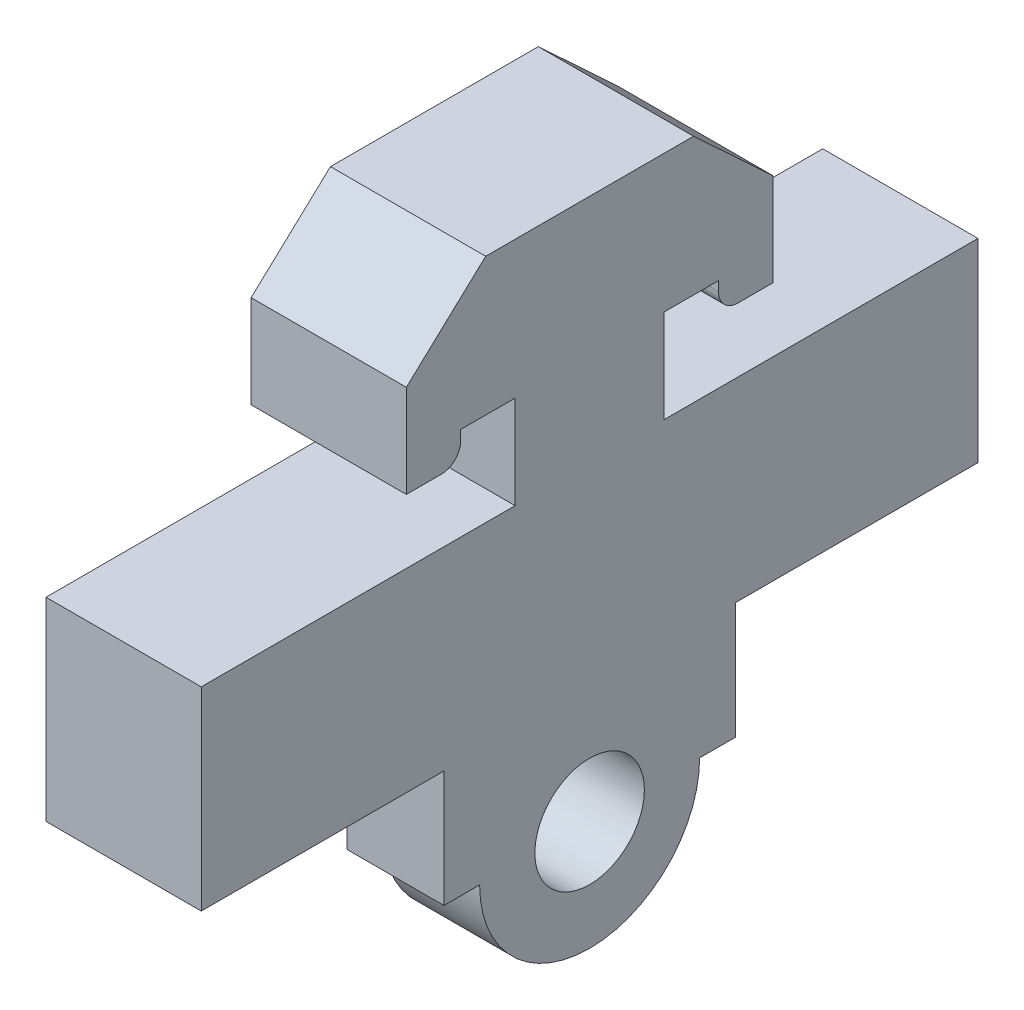
SolidWorks part; units mm, degrees
ref_plane "Front Plane" through (0, 0, 0) normal (0, 0, 1) x (1, 0, 0)
ref_plane "Top Plane" through (0, 0, 0) normal (0, 1, 0) x (1, 0, 0)
ref_plane "Right Plane" through (0, 0, 0) normal (1, 0, 0) x (0, 0, -1)
sketch "Sketch1" plane through (0, 0, 0) normal (0, 1, 0) x (1, 0, 0)
  line L1 (-37.5, -20) -> (37.5, -20)
  line L2 (-37.5, -20) -> (-37.5, 20)
  line L3 (-37.5, 20) -> (37.5, 20)
  line L4 (37.5, -20) -> (37.5, 20)
  line L5 (-37.5, -20) -> (37.5, 20) construction
  line L6 (-37.5, 20) -> (37.5, -20) construction
  point P0 (0, 0)
  dimension "D1" = 40
  dimension "D2" = 75
extrude "Boss-Extrude1" add sketch "Sketch1" along normal blind 10
sketch "Sketch2" plane through (37.5, 0, 0) normal (1, 0, 0) x (0, 0, -1)
  line L0 (-7.5, 0) -> (-7.5, -6)
  line L1 (-20, 0) -> (20, 0) construction
  line L2 (-7.5, -6) -> (-5.665, -6)
  line L3 (7.5, -6) -> (7.5, 0)
  line L5 (0, 0) -> (0, 1.9909) construction
  line L6 (5.665, -6) -> (7.5, -6)
  line L7 (-2.82, -6) -> (2.82, -6)
  line L8 (-20, 0) -> (-7.5, 0)
  line L9 (7.5, 0) -> (20, 0)
  line L12 (-20, 0) -> (20, 0)
  line L13 (20, 0) -> (20, 10)
  line L14 (20, 10) -> (-20, 10)
  line L15 (-20, 10) -> (-20, 0)
  line L17 (20, 0) -> (20, 10)
  line L18 (20, 10) -> (-20, 10)
  line L19 (-20, 10) -> (-20, 0)
  circle A0 centre (0, -6) radius 2.82
  arc A1 (-5.665, -6) -> (5.665, -6) centre (0, -6) ccw
  dimension "D1" = 5.64
  dimension "D2" = 11.33
  dimension "D4" = 7.5
  dimension "D3" = 6
  dimension "D5" = 0
extrude "Boss-Extrude2" add sketch "Sketch2" along normal blind 5
mirror "Mirror1" about plane through (0, 0, 0) normal (1, 0, 0) of "Boss-Extrude2"
sketch "Sketch3" plane through (-42.5, 0, 0) normal (-1, 0, 0) x (0, 0, 1)
  line L0 (-4.1618, 10) -> (3.8382, 10)
  line L1 (-20, 10) -> (20, 10) construction
  line L2 (3.8382, 10) -> (3.8382, 14.8)
  line L3 (3.8382, 14.8) -> (6.6382, 14.8)
  line L4 (6.6382, 14.8) -> (6.6382, 14.3)
  line L5 (7.6382, 13.3) -> (9.4382, 13.3)
  line L6 (9.4382, 18.08) -> (9.4382, 14.8)
  line L7 (9.4382, 18.08) -> (5.3521, 21.88)
  line L8 (0, 10) -> (0, 13.289) construction
  line L9 (0, 0) -> (0, 3.0083) construction
  line L10 (9.4382, 14.8) -> (9.4382, 13.3)
  line L11 (-9.4382, 18.08) -> (-5.3521, 21.88)
  line L12 (-9.4382, 18.08) -> (-9.4382, 14.8)
  line L13 (-9.4382, 14.8) -> (-9.4382, 13.3)
  line L14 (-6.6382, 14.8) -> (-6.6382, 14.3)
  line L15 (-7.6382, 13.3) -> (-9.4382, 13.3)
  line L16 (-3.8382, 14.8) -> (-6.6382, 14.8)
  line L17 (-3.8382, 10) -> (-3.8382, 14.8)
  line L18 (-5.3521, 21.88) -> (5.3521, 21.88)
  arc A0 (6.6382, 14.3) -> (7.6382, 13.3) centre (7.6382, 14.3) ccw
  arc A1 (-6.6382, 14.3) -> (-7.6382, 13.3) centre (-7.6382, 14.3) cw
  line M10 (20, 10) -> (-20, 10)
  dimension "D9" = 1
  dimension "D1" = 8
  dimension "D2" = 4.8
  dimension "D3" = 1.5
  dimension "D4" = 3.28
  dimension "D5" = 3.8
  dimension "D6" = 5.58
  dimension "D7" = 2.8
  dimension "D8" = 5.6
extrude "Boss-Extrude3" add sketch "Sketch3" against normal up to surface (85 mm away) contours A1 L14 L16 L17 L2 L3 L4 A0 L5 L10 L6 L7 L18 L11 L12 L13 L15 M10 up to face at (42.5, -6, -2.82)
sketch "Sketch4" plane through (0, 21.88, 0) normal (0, 1, 0) x (1, 0, 0)
  line L1 (34.5049, 20) -> (-42.5, 20)
  line L2 (34.5049, 20) -> (34.5049, -20)
  line L3 (34.5049, -20) -> (-42.5, -20)
  line L4 (-42.5, 20) -> (-42.5, -20)
  point P4 (0, 0)
  point P6 (0, 0)
  point P8 (0, 0)
  point P10 (34.5049, -20)
extrude "Cut-Extrude1" cut sketch "Sketch4" against normal blind 72
